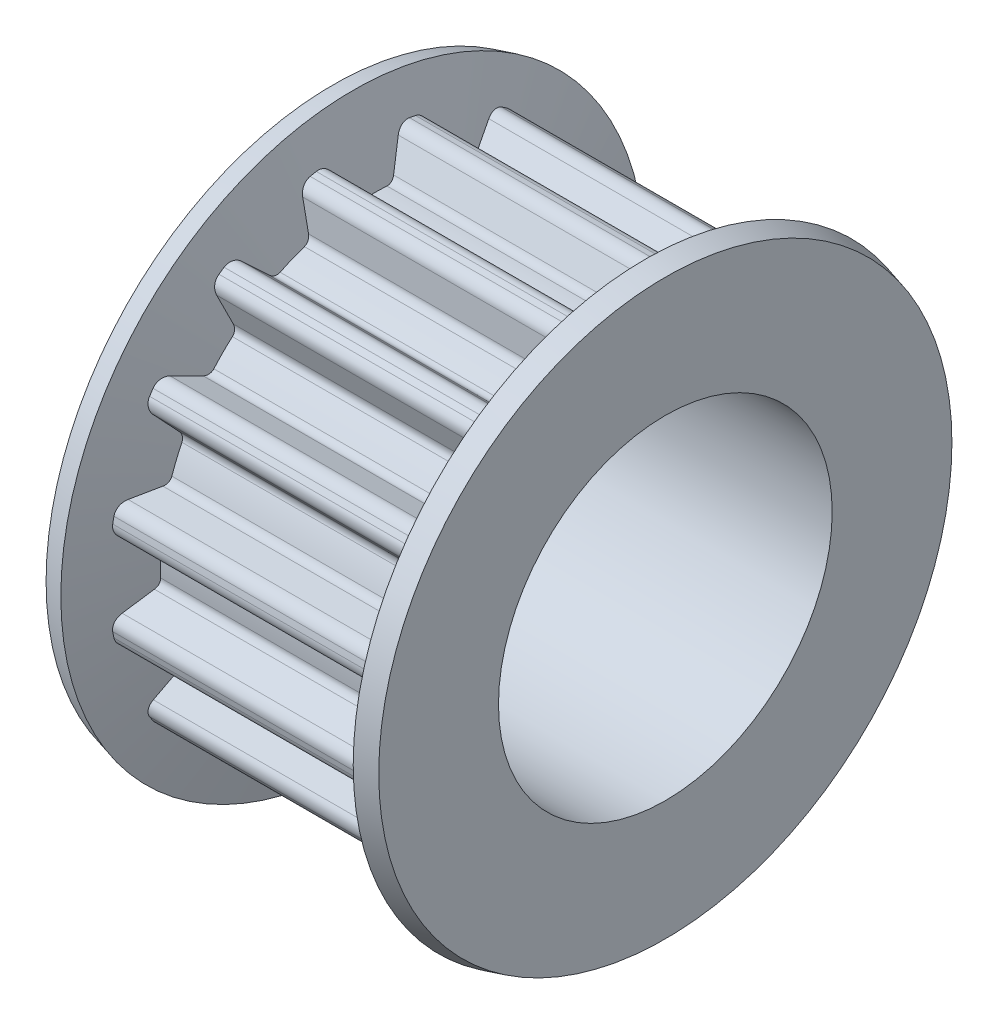
SolidWorks part; units mm, degrees
ref_plane "Front" through (0, 0, 0) normal (0, 0, 1) x (1, 0, 0)
ref_plane "Top" through (0, 0, 0) normal (0, 1, 0) x (1, 0, 0)
ref_plane "Right" through (0, 0, 0) normal (1, 0, 0) x (0, 0, -1)
sketch "Support-Cog" plane through (0, 0, 0) normal (1, 0, 0) x (0, 0, -1)
  line L0 (0, 0) -> (0, 6.1) construction
  line L3 (0.8861, 6.0353) -> (0.45, 5.1)
  line L4 (-0.8861, 6.0353) -> (-0.45, 5.1)
  line L5 (0.45, 5.1) -> (-0.45, 5.1) construction
  circle A1 centre (0, 0) radius 5.1198 construction
  circle A2 centre (0, 0) radius 6.1 construction
  arc A5 (0.7898, 5.8288) -> (1.1166, 5.9969) centre (1.0617, 5.702) cw
  arc A6 (-0.7898, 5.8288) -> (-1.1166, 5.9969) centre (-1.0617, 5.702) ccw
  circle A7 centre (0, 0) radius 4
  arc A8 (0.5084, 5.2252) -> (0.3148, 5.1101) centre (0.3271, 5.3097) cw
  arc A9 (-0.5084, 5.2252) -> (-0.3148, 5.1101) centre (-0.3271, 5.3097) ccw
  dimension "D1" = 50
  dimension "D2" = 0.9
  dimension "Diam-Gear" = 12.2
  dimension "Diam-Hole-Shaft" = 8
  dimension "D4" = 0.3
  dimension "D5" = 0.2
  dimension "D3" = 1
sketch "Support-Front" plane through (0, 0, 0) normal (0, 0, 1) x (1, 0, 0)
  line L0 (0, 0) -> (16, 0) construction
  line L1 (0, -4) -> (16, -4)
  line L2 (16, -7) -> (16, 7)
  line L3 (16, 7) -> (7.75, 7)
  line L4 (7.75, 7) -> (7.75, 6.1)
  line L5 (7.75, 6.1) -> (0, 6.1)
  line L6 (0, 6.1) -> (0, -6.1)
  line L7 (3.875, 6.1) -> (3.875, 0) construction
  line L8 (7.75, -6.1) -> (0, -6.1)
  line L9 (7.75, 7) -> (7.75, -7) construction
  line L10 (16, -7) -> (7.75, -7)
  line L11 (0, 6.1) -> (0, 7)
  line L12 (0, 4) -> (16, 4)
  line L13 (7.75, 6.1) -> (7.75, 7)
  line L14 (-0.1127, 6.8706) -> (0, 6.4501)
  line L15 (7.75, -7) -> (7.75, -6.1)
  line L16 (7.75, -6.1) -> (7.75, -7)
  line L17 (0, 6.4501) -> (0, 2.5423)
  line L18 (0.5, 2.5423) -> (0, 2.5423)
  line L19 (7.75, 2.5423) -> (7.75, 6.1)
  line L20 (0, -2.5423) -> (0, -6.1)
  line L21 (7.25, 6.5159) -> (7.25, 6.4501)
  line L22 (0, 2.5423) -> (0, 6.1)
  line L23 (7.75, -6.1) -> (7.75, -7)
  line L24 (7.8627, 6.8706) -> (7.3797, 7)
  line L25 (7.75, -7) -> (7.75, -6.1)
  line L26 (7.3797, 7) -> (7.25, 6.5159)
  line L27 (0.5, 2.5423) -> (0.5, 6.4501)
  line L28 (0.5, 6.4501) -> (0, 6.1) construction
  line L29 (7.75, 6.1) -> (7.75, 7)
  line L30 (0.5, 2.5423) -> (0, 6.1) construction
  line L31 (0, 6.4501) -> (0.5, 6.4501) construction
  line L34 (7.75, 6.4501) -> (7.25, 6.4501) construction
  line L35 (7.25, 2.5423) -> (7.25, 6.4501)
  line L36 (7.75, -2.5423) -> (7.75, -6.1)
  line L37 (7.75, 2.5423) -> (7.75, 6.1)
  line L38 (7.25, 2.5423) -> (7.75, 2.5423)
  line L39 (0.3703, 7) -> (0.5, 6.5159)
  line L40 (7.75, 6.4501) -> (7.75, 2.5423)
  line L41 (-0.1127, 6.8706) -> (0.3703, 7)
  line L42 (7.8627, 6.8706) -> (7.75, 6.4501)
  line L43 (7.75, 6.1) -> (7.75, 7)
  line L44 (0.5, -6.5159) -> (0.5, -6.4501)
  line L45 (7.75, -6.1) -> (7.75, -7)
  line L46 (7.8627, -6.8706) -> (7.75, -6.4501)
  line L47 (-0.1127, -6.8706) -> (0.3703, -7)
  line L48 (7.75, -6.4501) -> (7.75, -2.5423)
  line L49 (0.5, 6.5159) -> (0.5, 6.4501)
  line L50 (0.3703, -7) -> (0.5, -6.5159)
  line L51 (7.25, -2.5423) -> (7.75, -2.5423)
  line L52 (7.75, -2.5423) -> (7.75, -6.1)
  line L53 (7.25, -2.5423) -> (7.25, -6.4501)
  line L54 (7.75, -6.4501) -> (7.25, -6.4501) construction
  line L55 (0, -6.4501) -> (0.5, -6.4501) construction
  line L56 (7.75, -6.1) -> (7.75, -7)
  line L57 (0.5, -2.5423) -> (0.5, -6.4501)
  line L58 (7.3797, -7) -> (7.25, -6.5159)
  line L59 (7.8627, -6.8706) -> (7.3797, -7)
  line L60 (0, -2.5423) -> (0, -6.1)
  line L61 (7.25, -6.5159) -> (7.25, -6.4501)
  line L62 (7.75, -2.5423) -> (7.75, -6.1)
  line L63 (0.5, -2.5423) -> (0, -2.5423)
  line L64 (0, -6.4501) -> (0, -2.5423)
  line L65 (-0.1127, -6.8706) -> (0, -6.4501)
  line L66 (7.75, -6.1) -> (7.75, -7)
  line L67 (0, -6.1) -> (0, -7)
  line L68 (7.75, -6.1) -> (0, -6.1)
  line L69 (7.75, -7) -> (7.75, -6.1)
  line L70 (0, 6.4501) -> (0.5, 6.5159) construction
  dimension "D1" = 55
  dimension "Diam-Hub" = 14
  dimension "D2" = 8
  dimension "D3" = 15
  dimension "Width-Total" = 16
  dimension "Width-Cog" = 7.75
  dimension "Thickn-Flange" = 0.5
  dimension "Diam-Flange" = 14
sketch "Support-Key" plane through (0, 0, 0) normal (1, 0, 0) x (0, 0, -1)
  line L0 (0, -4) -> (0, 196) construction
  line L1 (0, 0) -> (0, 6.1) construction
  line L2 (1, 196) -> (-1, 196)
  line L3 (-1, 196) -> (-1, 0)
  line L4 (1, 196) -> (1, 0)
  line L5 (-1, 0) -> (1, 0)
  circle A0 centre (0, 0) radius 4 construction
  point P12 (0, 0)
  dimension "Height-Key" = 200
  dimension "Width-Key" = 2
sketch "Support-Stop-Screw" plane through (0, 0, 0) normal (0, 0, 1) x (1, 0, 0)
  line L0 (11.875, 0) -> (11.875, 196) construction
  line L1 (0, 0) -> (16, 0) construction
  line L2 (0, 0) -> (0, 6.1) construction
  line L3 (12.875, 196) -> (0, 196) construction
  line L4 (10.875, 196) -> (12.875, 196)
  line L5 (12.875, 196) -> (12.875, 0)
  line L6 (10.875, 196) -> (10.875, 0)
  line L7 (12.875, 0) -> (10.875, 0)
  line L8 (0, -4) -> (0, 196) construction
  dimension "Dist-Hole-Stop-Screw" = 11.875
  dimension "Diam-Stop-Screw" = 2
sketch "Sketch2" plane through (0, 0, 0) normal (0, 0, 1) x (1, 0, 0)
  line L5 (0, 0) -> (16, 0) construction
  line L10 (7.75, 6.1) -> (0, 6.1) construction
  line L11 (0, 0) -> (0, 6.1) construction
  line L12 (0, 0) -> (7.75, 0)
  line L13 (7.75, 0) -> (7.75, 6.1)
  line L15 (7.75, 6.1) -> (0, 6.1)
  line L16 (0, 0) -> (0, 6.1)
  line L17 (0, 0) -> (16, 0) construction
revolve "Body" add sketch "Sketch2" angle 360 about L17
sketch "Sketch6" plane through (0, 0, 0) normal (1, 0, 0) x (0, 0, -1)
  line L0 (0.8861, 6.0353) -> (0.45, 5.1) construction
  line L1 (-0.8861, 6.0353) -> (-0.45, 5.1) construction
  line L2 (0.7898, 5.8288) -> (0.5084, 5.2252)
  line L3 (-0.7898, 5.8288) -> (-0.5084, 5.2252)
  arc A0 (0.3148, 5.1101) -> (0.5084, 5.2252) centre (0.3271, 5.3097) ccw construction
  circle A1 centre (0, 0) radius 5.1198 construction
  arc A2 (-0.5084, 5.2252) -> (-0.3148, 5.1101) centre (-0.3271, 5.3097) ccw construction
  arc A3 (-0.7898, 5.8288) -> (-1.1166, 5.9969) centre (-1.0617, 5.702) ccw construction
  circle A4 centre (0, 0) radius 6.1 construction
  arc A5 (1.1166, 5.9969) -> (0.7898, 5.8288) centre (1.0617, 5.702) ccw construction
  arc A6 (0.3148, 5.1101) -> (0.5084, 5.2252) centre (0.3271, 5.3097) ccw
  arc A7 (0.3148, 5.1101) -> (-0.3148, 5.1101) centre (0, 0) ccw
  arc A8 (-0.5084, 5.2252) -> (-0.3148, 5.1101) centre (-0.3271, 5.3097) ccw
  arc A9 (-0.7898, 5.8288) -> (-1.1166, 5.9969) centre (-1.0617, 5.702) ccw
  arc A10 (1.1166, 5.9969) -> (-1.1166, 5.9969) centre (0, 0) ccw
  arc A11 (1.1166, 5.9969) -> (0.7898, 5.8288) centre (1.0617, 5.702) ccw
extrude "Cog" cut sketch "Sketch6" along normal through all
pattern_circular "Pattern-Cog" count 16 over 360 about axis through (0, 0, 0) along (1, 0, 0) of "Cog"
sketch "Sketch3" plane through (0, 0, 0) normal (0, 0, 1) x (1, 0, 0)
  line L2 (16, 7) -> (7.75, 7) construction
  line L3 (16, -7) -> (16, 7) construction
  line L4 (7.75, 0) -> (16, 0)
  line L5 (16, 7) -> (7.75, 7)
  line L6 (7.75, 7) -> (7.75, 0)
  line L7 (0, 0) -> (16, 0) construction
  line L8 (0, 0) -> (16, 0) construction
  line L10 (16, 0) -> (16, 7)
revolve "Hub" [suppressed] add sketch "Sketch3" angle 360 about L8
sketch "Sketch15" plane through (0, 0, 0) normal (0, 0, 1) x (1, 0, 0)
  line L0 (11.875, 196) -> (11.875, 0) construction
  line L1 (11.875, 196) -> (12.875, 196)
  line L2 (12.875, 196) -> (12.875, 0)
  line L3 (12.875, 0) -> (11.875, 0)
  line L4 (11.875, 196) -> (11.875, 0)
revolve "Stop-Screw" [suppressed] cut sketch "Sketch15" angle 360 about L0
sketch "Sketch16" plane through (0, 0, 0) normal (0, 0, 1) x (1, 0, 0)
  line L0 (-0.1127, 6.8706) -> (-0.1127, 2.5423)
  line L2 (1.4261, 2.5423) -> (1.4261, 3.0595)
  line L7 (0.3703, 7) -> (0.5, 6.5159) construction
  line L10 (-0.1127, 6.8706) -> (0.3703, 7) construction
  line L11 (1.4261, 2.5423) -> (-0.1127, 2.5423)
  line L12 (0, 0) -> (16, 0) construction
  line L13 (0, 0) -> (16, 0) construction
  line L16 (0.3703, 7) -> (1.4261, 3.0595)
  line L19 (-0.1127, 6.8706) -> (0.3703, 7)
revolve "Flange-Left" add sketch "Sketch16" angle 360 about L13
sketch "Sketch17" plane through (0, 0, 0) normal (0, 0, 1) x (1, 0, 0)
  line L0 (0, 0) -> (16, 0) construction
  line L2 (7.8627, 6.8706) -> (7.3797, 7) construction
  line L3 (7.3797, 7) -> (7.25, 6.5159) construction
  line L4 (7.8627, 6.8706) -> (7.8627, 2.5423)
  line L5 (0, 0) -> (9, 0) construction
  line L6 (6.9067, 2.5423) -> (6.9067, 5.2347)
  line L11 (7.25, 2.5423) -> (7.75, 2.5423) construction
  line L14 (7.8627, 6.8706) -> (7.3797, 7)
  line L15 (7.3797, 7) -> (6.9067, 5.2347)
  line L18 (6.9067, 2.5423) -> (7.8627, 2.5423)
revolve "Flange-Right" add sketch "Sketch17" angle 360 about L5
sketch "Sketch8" plane through (0, 0, 0) normal (0, 0, 1) x (1, 0, 0)
  line L0 (16, -7) -> (16, 7) construction
  line L3 (16, 0) -> (16, -4)
  line L4 (-1.304, -4) -> (-1.304, 0)
  line L5 (-1.304, -4) -> (16, -4)
  line L6 (0, 0) -> (16, 0) construction
  line L7 (-1.304, 0) -> (16, 0) construction
  line L8 (-1.304, 0) -> (16, 0)
revolve "Hole-Shaft" cut sketch "Sketch8" angle 360 about L7
sketch "Sketch11" plane through (0, 0, 0) normal (1, 0, 0) x (0, 0, -1)
  line L4 (1, 196) -> (-1, 196)
  line L5 (-1, 196) -> (-1, 0)
  line L6 (-1, 0) -> (1, 0)
  line L7 (1, 0) -> (1, 196)
  line L8 (1, 196) -> (-1, 196)
  line L9 (-1, 196) -> (-1, 0)
  line L10 (-1, 0) -> (1, 0)
  line L11 (1, 0) -> (1, 196)
  dimension "D1" = 0
extrude "Key" [suppressed] cut sketch "Sketch11" along normal through all
pattern_circular "Pattern-Stop-Screw" [suppressed] count 2 every 90 about axis through (0, 0, 0) along (1, 0, 0)
equation "\"Dist-Hole-Stop-Screw@Support-Stop-Screw\"=\"Width-Cog@Support-Front\"+(\"Width-Total@Support-Front\"-\"Width-Cog@Support-Front\")/2"
